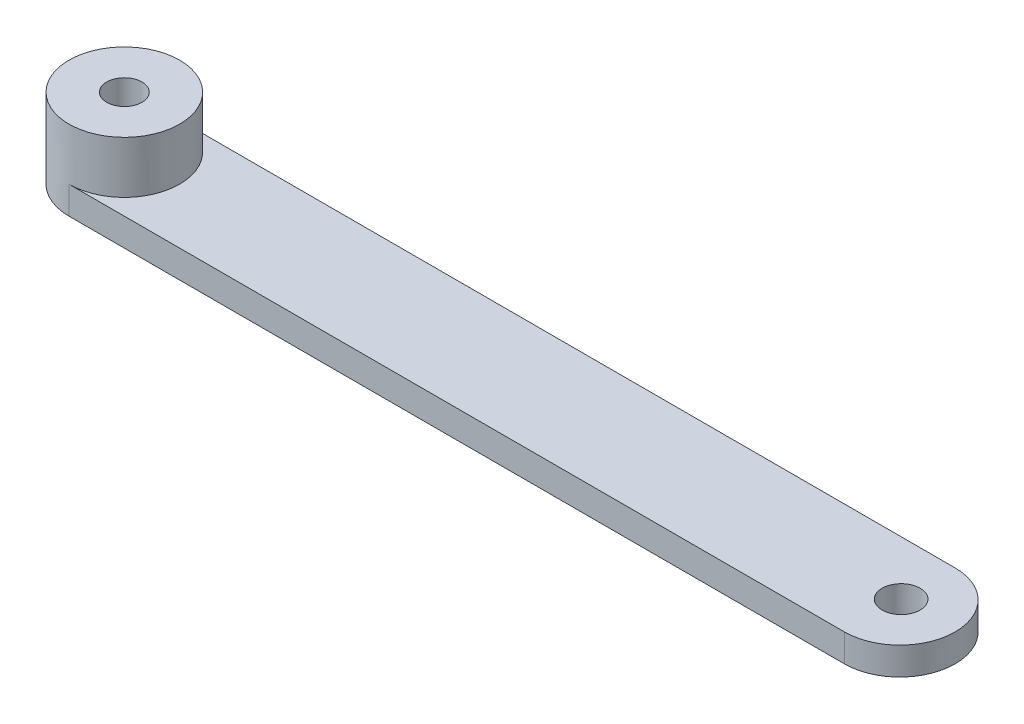
SolidWorks part; units mm, degrees
material "PET"
ref_plane "Front" through (0, 0, 0) normal (0, 0, 1) x (1, 0, 0)
ref_plane "Top" through (0, 0, 0) normal (0, 1, 0) x (1, 0, 0)
ref_plane "Right" through (0, 0, 0) normal (1, 0, 0) x (0, 0, -1)
sketch "Sketch1" plane through (0, 0, 0) normal (0, 1, 0) x (1, 0, 0)
  line L1 (-23.1719, 5.6259) -> (65.7281, 5.6259)
  line L3 (-23.1719, -7.0741) -> (65.7281, -7.0741)
  line L5 (-23.1719, 5.6259) -> (65.7281, -7.0741) construction
  line L6 (-23.1719, -7.0741) -> (65.7281, 5.6259) construction
  arc A0 (-23.1719, 5.6259) -> (-23.1719, -7.0741) centre (-23.1719, -0.7241) ccw
  arc A1 (65.7281, 5.6259) -> (65.7281, -7.0741) centre (65.7281, -0.7241) cw
  point P4 (21.2781, -0.7241)
  dimension "D1" = 6.35
  dimension "D2" = 88.9
extrude "Boss-Extrude1" add sketch "Sketch1" along normal blind 3.175
sketch "Sketch2" plane through (0, 3.175, 0) normal (0, 1, 0) x (1, 0, 0)
  line L0 (-23.1719, -0.5708) -> (40.067, -0.5708) construction
  circle A0 centre (-23.1719, -0.5708) radius 2.175
  circle A2 centre (65.7281, -0.5708) radius 2.175
  dimension "D1" = 4.35
  dimension "D2" = 88.9
  dimension "D3" = 4.35
extrude "Cut-Extrude1" cut sketch "Sketch2" against normal blind 12.7
sketch "Sketch3" plane through (0, 3.175, 0) normal (0, 1, 0) x (1, 0, 0)
  arc A0 (-23.1719, 5.6259) -> (-23.1719, -7.0741) centre (-23.1719, -0.7241) ccw
  circle A1 centre (-23.1719, -0.7241) radius 2.0217
  arc A2 (-23.1719, 5.6259) -> (-23.1719, -7.0741) centre (-23.1719, -0.7241) cw
extrude "Boss-Extrude2" add sketch "Sketch3" along normal blind 5.9625
